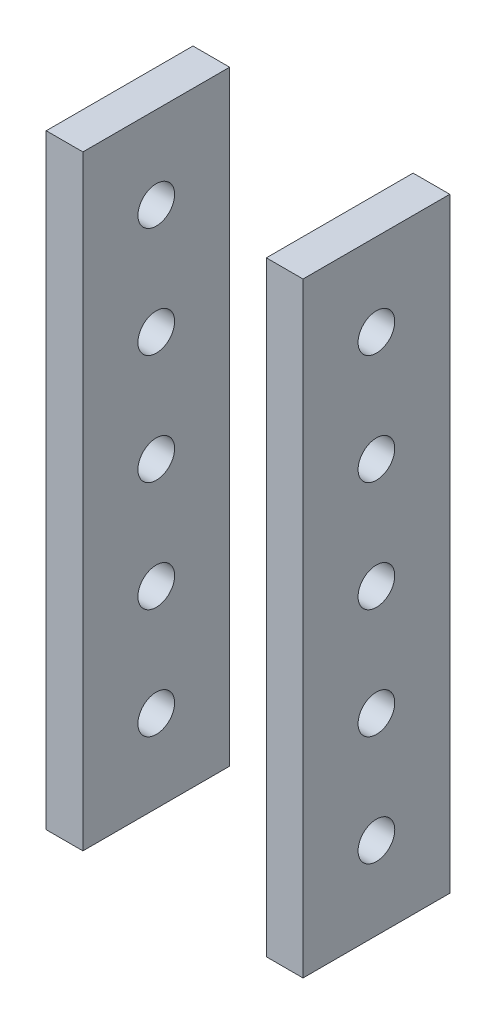
SolidWorks part; units mm, degrees
ref_plane "Front Plane" through (0, 0, 0) normal (0, 0, 1) x (1, 0, 0)
ref_plane "Top Plane" through (0, 0, 0) normal (0, 1, 0) x (1, 0, 0)
ref_plane "Right Plane" through (0, 0, 0) normal (1, 0, 0) x (0, 0, -1)
ref_plane "Plane1" through (-25, 0, 0) normal (1, 0, 0) x (0, 0, -1)
sketch "Sketch2" plane through (-25, 0, 0) normal (1, 0, 0) x (0, 0, -1)
  line L0 (0, 200) -> (0, -200) construction
  line L2 (-40, -211.6498) -> (-40, -236.6498)
  line L4 (0, 0.9816) -> (0, -236.6498)
  line L6 (-40, -211.6498) -> (-40, -141.6498)
  line L7 (-40, -141.6498) -> (0, -141.6498)
  line L8 (0, 0.9816) -> (0, -141.6498)
  line L9 (-20, -224.1498) -> (-20, -194.1498) construction
  line L11 (-40, -236.6498) -> (-40, -306.6498)
  line L12 (-40, -306.6498) -> (0, -306.6498)
  line L13 (0, -236.6498) -> (0, -306.6498)
  line L14 (-20, -224.1498) -> (-20, -254.1498) construction
  circle A1 centre (-20, -224.1498) radius 5
  circle A2 centre (-20, -194.1498) radius 5
  circle A3 centre (-20, -164.1498) radius 5
  circle A4 centre (-20, -254.1498) radius 5
  circle A5 centre (-20, -284.1498) radius 5
  dimension "D4" = 10
  dimension "D1" = 70
  dimension "D2" = 82.5
  dimension "D3" = 70
  dimension "D6" = 30
  dimension "D8" = 30
  dimension "D5" = 3
  dimension "D7" = 3
extrude "Boss-Extrude1" add sketch "Sketch2" against normal blind 10 contours L13 L4 L7 L6 L2 L11 L12 A5 A4 A3 A2 A1
mirror "Mirror2" about plane through (0, 0, 0) normal (1, 0, 0) of bodies 101
